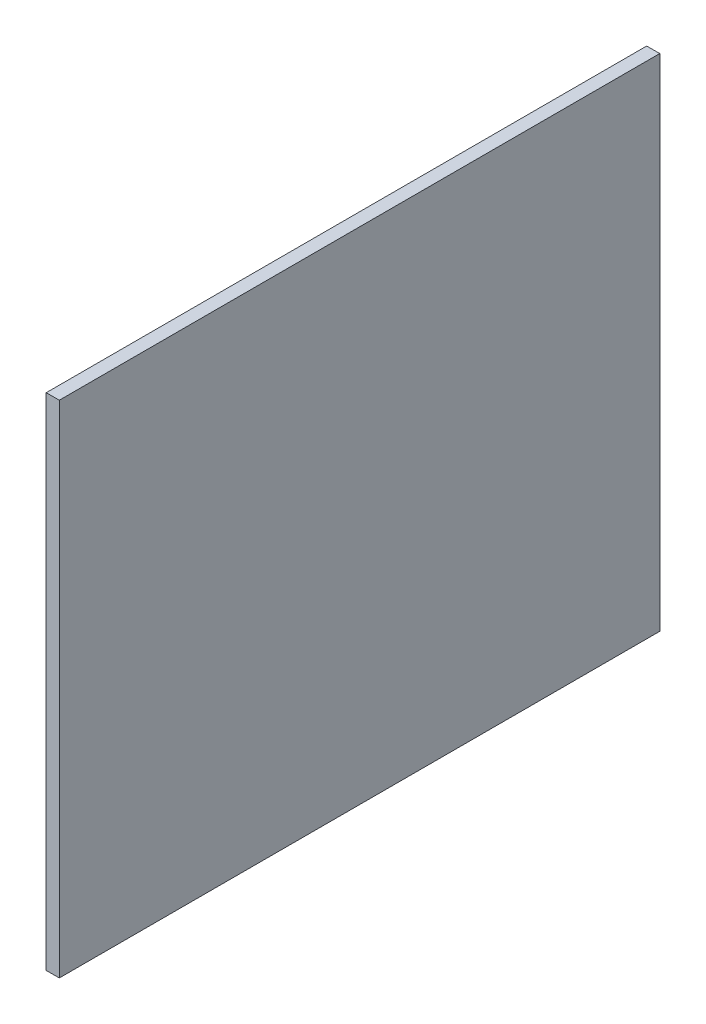
SolidWorks part; units mm, degrees
ref_plane "前视基准面" through (0, 0, 0) normal (0, 0, 1) x (1, 0, 0)
ref_plane "上视基准面" through (0, 0, 0) normal (0, 1, 0) x (1, 0, 0)
ref_plane "右视基准面" through (0, 0, 0) normal (1, 0, 0) x (0, 0, -1)
sketch "草图1" plane through (0, 0, 0) normal (1, 0, 0) x (0, 0, -1)
  line L1 (0, 0) -> (276, 0)
  line L2 (0, 0) -> (0, 230)
  line L3 (0, 230) -> (276, 230)
  line L4 (276, 0) -> (276, 230)
extrude "凸台-拉伸1" add sketch "草图1" along normal blind 6
